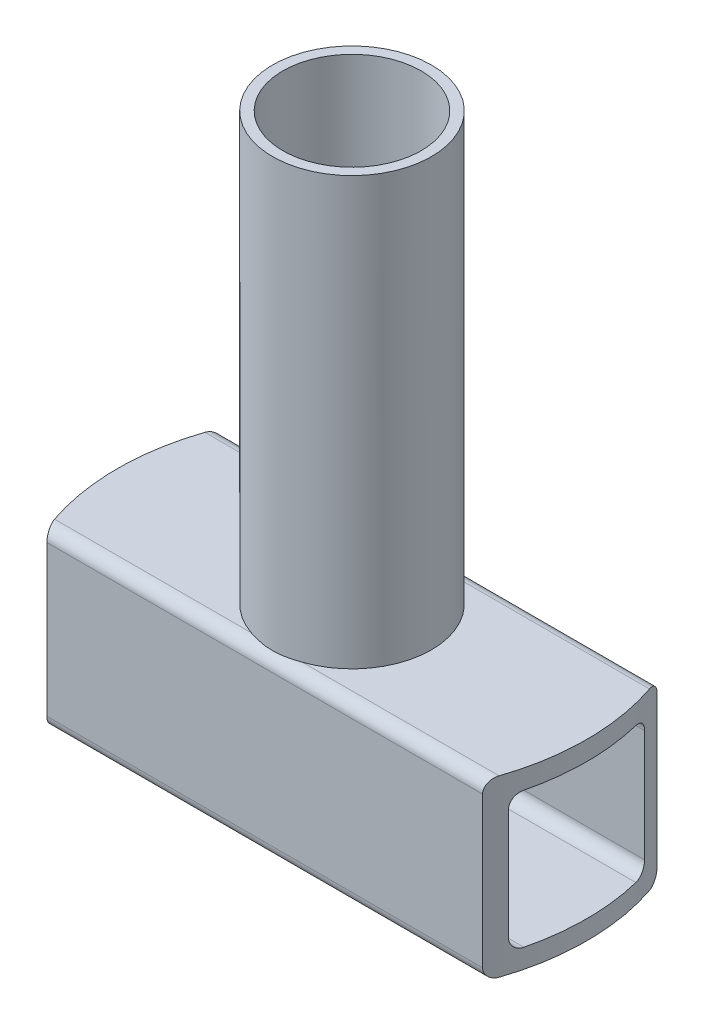
SolidWorks part; units mm, degrees
material "AISI 1020"
ref_plane "Front Plane" through (0, 0, 0) normal (0, 0, 1) x (1, 0, 0)
ref_plane "Top Plane" through (0, 0, 0) normal (0, 1, 0) x (1, 0, 0)
ref_plane "Right Plane" through (0, 0, 0) normal (1, 0, 0) x (0, 0, -1)
sketch "Sketch1" plane through (0, 0, 0) normal (1, 0, 0) x (0, 0, -1)
  line L0 (14.351, 14.351) -> (-14.351, 14.351)
  line L1 (18.415, -18.415) -> (-18.415, -18.415)
  line L2 (18.415, -18.415) -> (18.415, 18.415)
  line L3 (18.415, 18.415) -> (-18.415, 18.415)
  line L4 (-18.415, -18.415) -> (-18.415, 18.415)
  line L5 (18.415, -18.415) -> (-18.415, 18.415) construction
  line L6 (18.415, 18.415) -> (-18.415, -18.415) construction
  line L7 (-14.351, -14.351) -> (-14.351, 14.351)
  line L8 (14.351, -14.351) -> (-14.351, -14.351)
  line L9 (14.351, -14.351) -> (14.351, 14.351)
  point P0 (0, 0)
  dimension "1.45" = 36.83
  dimension "D2" = 36.83
  dimension "D3" = 4.064
extrude "Boss-Extrude1" add sketch "Sketch1" along normal mid plane 101.6
fillet "Fillet1" radius 2.54 8 edges at (0, -14.351, -14.351) (0, -14.351, 14.351) (0, 14.351, -14.351) (0, 14.351, 14.351) (0, -18.415, 18.415) (0, -18.415, -18.415) (0, 18.415, -18.415) (0, 18.415, 18.415)
sketch "Sketch3" plane through (0, 18.415, 0) normal (0, 1, 0) x (1, 0, 0)
  circle A0 centre (0, 0) radius 16.764
  dimension "D1" = 33.528
extrude "Cut-Extrude2" cut sketch "Sketch3" against normal through all
sketch "Sketch4" plane through (0, 18.415, 0) normal (0, 1, 0) x (1, 0, 0)
  line L1 (-50.8, 18.415) -> (50.8, 18.415)
  line L2 (-50.8, 18.415) -> (-50.8, -18.415)
  line L3 (-50.8, -18.415) -> (50.8, -18.415)
  line L4 (50.8, 18.415) -> (50.8, -18.415)
  circle A0 centre (0, 0) radius 49.53
  line M6 (50.8, 15.875) -> (5.3867, 15.875)
  line M8 (5.3867, -15.875) -> (50.8, -15.875)
  line M9 (50.8, -15.875) -> (50.8, 15.875)
  dimension "D1" = 99.06
extrude "Cut-Extrude3" cut sketch "Sketch4" against normal through all contours A0 L1 L2 L3 | A0 M8 M9 M6 | A0 L4 L1 M6 | A0 L3 L4 M8
sketch "Sketch5" plane through (0, -18.415, 0) normal (0, -1, 0) x (1, 0, 0)
  circle A0 centre (0, 0) radius 16.764
  arc A1 (5.3867, -15.875) -> (5.3867, 15.875) centre (0, 0) ccw construction
  circle A2 centre (0, 0) radius 14.605
  dimension "D1" = 29.21
extrude "Boss-Extrude2" add sketch "Sketch5" against normal blind 127
